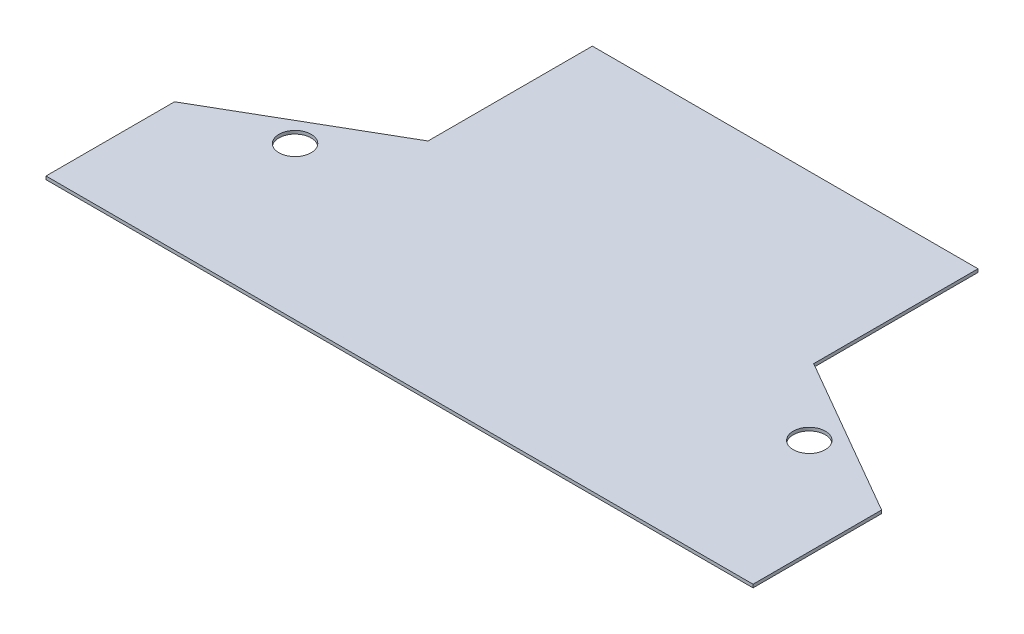
SolidWorks part; units mm, degrees
ref_plane "Front Plane" through (0, 0, 0) normal (0, 0, 1) x (1, 0, 0)
ref_plane "Top Plane" through (0, 0, 0) normal (0, 1, 0) x (1, 0, 0)
ref_plane "Right Plane" through (0, 0, 0) normal (1, 0, 0) x (0, 0, -1)
sketch "Sketch1" plane through (0, 0, 0) normal (0, 1, 0) x (1, 0, 0)
  line L0 (-22, 4) -> (-17, 6.887)
  line L1 (0, 0) -> (-22, 0)
  line L2 (0, 0) -> (0, 4)
  line L4 (-22, 0) -> (-22, 4)
  line L6 (-17, 6.887) -> (-17, 12)
  line L7 (-17, 12) -> (-5, 12)
  line L8 (-5, 6.887) -> (-5, 12)
  line L9 (0, 4) -> (-5, 6.887)
  circle A0 centre (-19, 4.75) radius 0.5
  circle A1 centre (-3, 4.75) radius 0.5
  dimension "D5" = 1
  dimension "D1" = 4
  dimension "D2" = 22
  dimension "D3" = 12
  dimension "D4" = 2.887
  dimension "D6" = 5.113
  dimension "D7" = 5.113
  dimension "D8" = 0.75
  dimension "D9" = 3
  dimension "D10" = 2
extrude "Boss-Extrude1" add sketch "Sketch1" along normal blind 0.1
